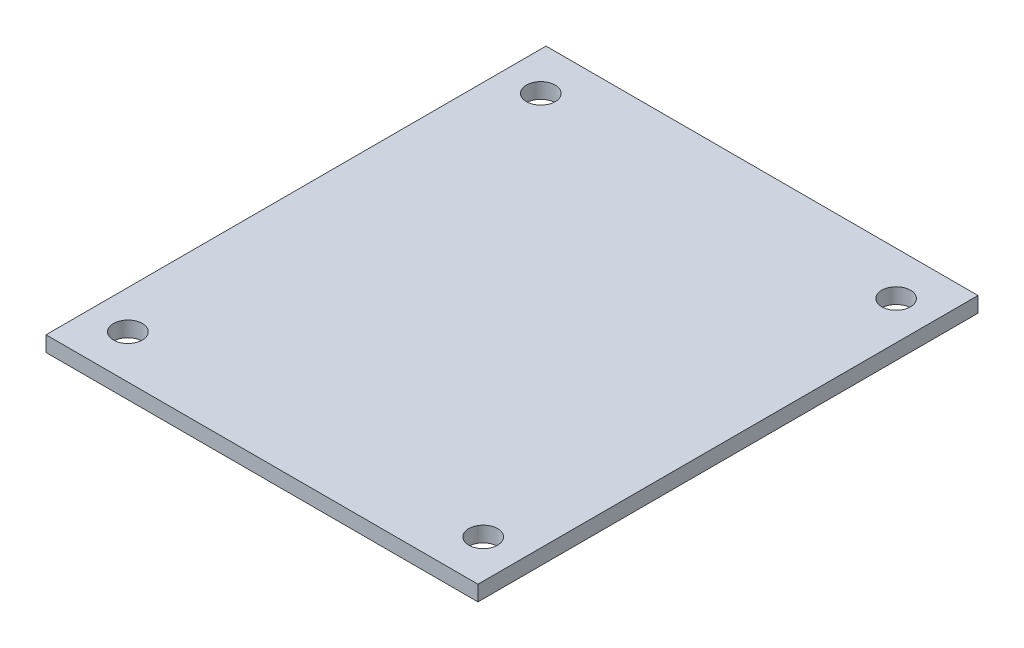
SolidWorks part; units mm, degrees
ref_plane "Front Plane" through (0, 0, 0) normal (0, 0, 1) x (1, 0, 0)
ref_plane "Top Plane" through (0, 0, 0) normal (0, 1, 0) x (1, 0, 0)
ref_plane "Right Plane" through (0, 0, 0) normal (1, 0, 0) x (0, 0, -1)
sketch "Sketch1" plane through (0, 0, 0) normal (0, 1, 0) x (1, 0, 0)
  line L1 (0, 0) -> (44.9834, 0)
  line L2 (0, 0) -> (0, 52.07)
  line L3 (0, 52.07) -> (44.9834, 52.07)
  line L4 (44.9834, 0) -> (44.9834, 52.07)
  circle A0 centre (3.9917, 47.535) radius 1.5
  circle A1 centre (40.9917, 47.535) radius 1.5
  circle A2 centre (40.9917, 4.535) radius 1.5
  circle A3 centre (3.9917, 4.535) radius 1.5
  dimension "D5" = 3
  dimension "D1" = 44.9834
  dimension "D2" = 52.07
  dimension "D3" = 43
  dimension "D4" = 37
  dimension "D6" = 3.9917
  dimension "D7" = 4.535
extrude "Boss-Extrude1" add sketch "Sketch1" along normal blind 1.6
equation "\"D6@Sketch1\"=(\"D1@Sketch1\"-\"D4@Sketch1\")/2"
equation "\"D7@Sketch1\"=(\"D2@Sketch1\"-\"D3@Sketch1\")/2"
